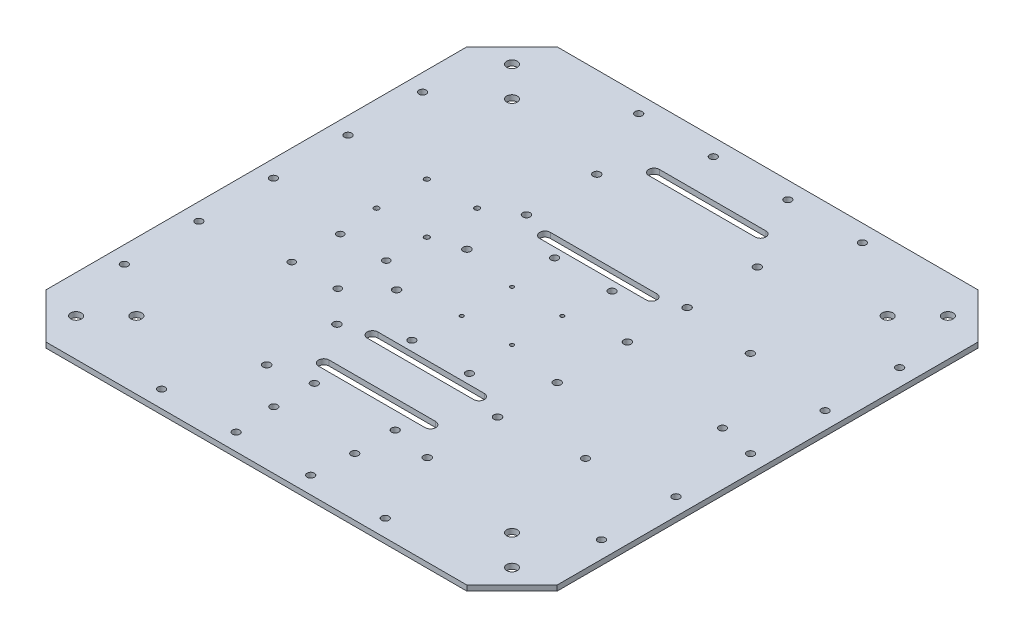
SolidWorks part; units mm, degrees
ref_plane "Front Plane" through (0, 0, 0) normal (0, 0, 1) x (1, 0, 0)
ref_plane "Top Plane" through (0, 0, 0) normal (0, 1, 0) x (1, 0, 0)
ref_plane "Right Plane" through (0, 0, 0) normal (1, 0, 0) x (0, 0, -1)
sketch "Sketch1" plane through (0, 0, 0) normal (0, 1, 0) x (1, 0, 0)
  line L0 (-121.2861, 45.3182) -> (-94.3453, 72.259)
  line L1 (-121.2861, 72.259) -> (183.5139, 72.259)
  line L2 (-121.2861, 72.259) -> (-121.2861, -232.541)
  line L3 (-121.2861, -232.541) -> (183.5139, -232.541)
  line L4 (183.5139, 72.259) -> (183.5139, -232.541)
  line L5 (31.1139, 95.069) -> (31.1139, -294.9418) construction
  line L6 (-146.0448, -80.141) -> (218.038, -80.141) construction
  line L7 (183.5139, 45.3182) -> (156.5732, 72.259)
  line L8 (183.5139, -205.6003) -> (156.5732, -232.541)
  line L9 (-121.2861, -205.6003) -> (-94.3453, -232.541)
  point P8 (31.1139, 72.259)
  point P11 (-121.2861, -80.141)
  dimension "D1" = 304.8
  dimension "D2" = 304.8
  dimension "D3" = 45
  dimension "D4" = 38.1
extrude "Boss-Extrude1" add sketch "Sketch1" along normal blind 3.175
sketch "Sketch2" plane through (0, 3.175, 0) normal (0, 1, 0) x (1, 0, 0)
  line L0 (31.1139, 72.259) -> (31.1139, -287.8465) construction
  line L1 (-94.3453, 72.259) -> (156.5732, 72.259) construction
  line L2 (183.5139, -80.141) -> (-158.2106, -80.141) construction
  line L3 (183.5139, 45.3182) -> (183.5139, -205.6003) construction
  circle A0 centre (13.8419, -37.469) radius 2.159
  circle A1 centre (48.1319, -37.469) radius 2.159
  circle A2 centre (13.8419, -122.559) radius 2.159
  circle A3 centre (48.1319, -122.559) radius 2.159
  dimension "D5" = 4.318
  dimension "D6" = 4.318
  dimension "D7" = 4.318
  dimension "D8" = 4.318
  dimension "D1" = 17.272
  dimension "D2" = 34.29
  dimension "D3" = 85.09
  dimension "D4" = 42.672
extrude "Cut-Extrude1" cut sketch "Sketch2" against normal through all
sketch "Sketch4" plane through (0, 3.175, 0) normal (0, 1, 0) x (1, 0, 0)
  line L0 (-0.6361, 36.294) -> (62.8639, 36.294) construction
  line L1 (-0.6361, 39.469) -> (62.8639, 39.469)
  line L2 (-0.6361, 33.119) -> (62.8639, 33.119)
  line L3 (-0.6361, -28.706) -> (62.8639, -28.706) construction
  line L4 (-0.6361, -25.531) -> (62.8639, -25.531)
  line L5 (-0.6361, -31.881) -> (62.8639, -31.881)
  line L6 (31.1139, 72.259) -> (31.1139, -65.9651) construction
  line L7 (-94.3453, 72.259) -> (156.5732, 72.259) construction
  line L8 (-121.2861, -80.141) -> (257.7387, -80.141) construction
  line L9 (-121.2861, 45.3182) -> (-121.2861, -205.6003) construction
  line L10 (31.1139, -232.541) -> (31.1139, -94.317) construction
  line L11 (-0.6361, -131.576) -> (62.8639, -131.576) construction
  line L12 (-0.6361, -128.401) -> (62.8639, -128.401)
  line L13 (-0.6361, -134.751) -> (62.8639, -134.751)
  line L14 (-0.6361, -160.576) -> (62.8639, -160.576) construction
  line L15 (-0.6361, -157.401) -> (62.8639, -157.401)
  line L16 (-0.6361, -163.751) -> (62.8639, -163.751)
  arc A0 (-0.6361, 39.469) -> (-0.6361, 33.119) centre (-0.6361, 36.294) ccw
  arc A1 (62.8639, 33.119) -> (62.8639, 39.469) centre (62.8639, 36.294) ccw
  arc A2 (-0.6361, -25.531) -> (-0.6361, -31.881) centre (-0.6361, -28.706) ccw
  arc A3 (62.8639, -31.881) -> (62.8639, -25.531) centre (62.8639, -28.706) ccw
  arc A5 (-0.6361, -128.401) -> (-0.6361, -134.751) centre (-0.6361, -131.576) ccw
  arc A6 (62.8639, -134.751) -> (62.8639, -128.401) centre (62.8639, -131.576) ccw
  arc A7 (-0.6361, -157.401) -> (-0.6361, -163.751) centre (-0.6361, -160.576) ccw
  arc A8 (62.8639, -163.751) -> (62.8639, -157.401) centre (62.8639, -160.576) ccw
  point P2 (31.1139, 36.294)
  point P7 (31.1139, -28.706)
  point P28 (31.1139, -131.576)
  point P33 (31.1139, -160.576)
  dimension "D1" = 63.5
  dimension "D2" = 63.5
  dimension "D3" = 6.35
  dimension "D4" = 6.35
  dimension "D5" = 65
  dimension "D6" = 48.26
  dimension "D7" = 63.5
  dimension "D8" = 63.5
  dimension "D9" = 6.35
  dimension "D10" = 6.35
  dimension "D11" = 29
  dimension "D12" = 48.26
extrude "Cut-Extrude2" cut sketch "Sketch4" against normal through all
sketch "Sketch7" plane through (0, 3.175, 0) normal (0, 1, 0) x (1, 0, 0)
  line L0 (-49.9121, 53.9596) -> (-49.9121, -59.6418) construction
  line L1 (-121.2861, -80.141) -> (183.5139, -80.141) construction
  line L2 (-121.2861, 45.3182) -> (-121.2861, -205.6003) construction
  line L3 (183.5139, 45.3182) -> (183.5139, -205.6003) construction
  line L4 (31.1139, 72.259) -> (31.1139, -252.674) construction
  line L5 (-94.3453, 72.259) -> (156.5732, 72.259) construction
  circle A0 centre (-34.9261, -34.929) radius 1.524
  circle A1 centre (-34.9261, -64.901) radius 1.524
  circle A2 centre (-64.8981, -64.901) radius 1.524
  circle A3 centre (-64.8981, -34.929) radius 1.524
  dimension "D1" = 3.048
  dimension "D2" = 14.986
  dimension "D4" = 29.972
  dimension "D3" = 3.048
  dimension "D5" = 15.24
  dimension "D6" = 66.04
  dimension "D7" = 14.986
extrude "Cut-Extrude3" cut sketch "Sketch7" against normal through all
sketch "Sketch8" plane through (0, 3.175, 0) normal (0, 1, 0) x (1, 0, 0)
  line L0 (-94.3453, -232.541) -> (156.5732, -232.541) construction
  line L1 (183.5139, 45.3182) -> (183.5139, -205.6003) construction
  circle A0 centre (73.0239, -207.649) radius 1.524
  circle A1 centre (73.0239, -177.169) radius 1.524
  circle A2 centre (96.8999, -207.649) radius 1.524
  circle A3 centre (96.8999, -177.169) radius 1.524
  dimension "D1" = 3.048
  dimension "D2" = 30.48
  dimension "D3" = 23.876
  dimension "D4" = 24.892
  dimension "D5" = 86.614
extrude "Cut-Extrude4" [suppressed] cut sketch "Sketch8" against normal through all and the other way through all
sketch "Sketch10" plane through (0, 0, 0) normal (0, -1, 0) x (1, 0, 0)
  line L0 (-94.3453, 232.541) -> (156.5732, 232.541) construction
  line L1 (31.1139, 232.541) -> (31.1139, 128.7119) construction
  line L2 (-0.6361, 163.751) -> (62.8639, 163.751) construction
  circle A0 centre (6.9839, 198.041) radius 2.159
  circle A1 centre (55.2439, 198.041) radius 2.159
  circle A2 centre (6.9839, 173.911) radius 2.159
  circle A3 centre (55.2439, 173.911) radius 2.159
  dimension "D1" = 4.318
  dimension "D2" = 48.26
  dimension "D4" = 10.16
  dimension "D6" = 4.318
  dimension "D7" = 4.318
  dimension "D8" = 4.318
  dimension "D3" = 24.13
  dimension "D5" = 24.13
extrude "Cut-Extrude6" cut sketch "Sketch10" against normal through all
sketch "Sketch9" plane through (0, 0, 0) normal (0, -1, 0) x (-1, 0, 0)
  line L1 (121.2861, -80.141) -> (-327.4314, -80.141) construction
  line L2 (48.6421, -47.3693) -> (48.6421, -130.2963) construction
  line L3 (-31.1139, 72.259) -> (-31.1139, -331.7119) construction
  line L4 (94.3453, 72.259) -> (-156.5732, 72.259) construction
  line L7 (121.2861, 45.3182) -> (121.2861, -205.6003) construction
  circle A0 centre (62.3581, -117.987) radius 2.032
  circle A1 centre (34.9261, -117.987) radius 2.032
  circle A2 centre (62.3581, -89.031) radius 2.032
  circle A3 centre (34.9261, -89.031) radius 2.032
  dimension "D1" = 4.064
  dimension "D9" = 4.064
  dimension "D2" = 66.04
  dimension "D3" = 28.956
  dimension "D4" = 8.89
  dimension "D8" = 13.716
extrude "Cut-Extrude5" cut sketch "Sketch9" against normal through all
sketch "Sketch13" plane through (0, 0, 0) normal (0, -1, 0) x (1, 0, 0)
  line L0 (31.1139, -72.259) -> (31.1139, 261.4711) construction
  line L1 (-94.3453, -72.259) -> (156.5732, -72.259) construction
  line L2 (-121.2861, 80.141) -> (239.2508, 80.141) construction
  line L3 (-121.2861, -45.3182) -> (-121.2861, 205.6003) construction
  circle A0 centre (16.1139, 95.141) radius 1.1
  circle A1 centre (16.1139, 65.141) radius 1.1
  circle A2 centre (46.1139, 65.141) radius 1.1
  circle A3 centre (46.1139, 95.141) radius 1.1
  dimension "D1" = 2.2
  dimension "D2" = 2.2
  dimension "D3" = 30
  dimension "D4" = 15
  dimension "D5" = 15
extrude "Cut-Extrude8" cut sketch "Sketch13" against normal through all
sketch "Sketch14" plane through (0, 0, 0) normal (0, -1, 0) x (1, 0, 0)
  line L0 (31.1139, 232.541) -> (31.1139, -154.5354) construction
  line L1 (-94.3453, 232.541) -> (156.5732, 232.541) construction
  line L2 (-121.2861, 80.141) -> (331.9066, 80.141) construction
  line L3 (-121.2861, -45.3182) -> (-121.2861, 205.6003) construction
  line L4 (-121.2861, 205.6003) -> (-94.3453, 232.541) construction
  line L5 (-224.559, -175.5319) -> (286.7869, 335.814) construction
  line L6 (-224.559, -175.5319) -> (286.7869, -175.5319) construction
  line L7 (-224.559, -175.5319) -> (-224.559, 335.814) construction
  line L8 (-121.2861, 205.6003) -> (-94.3453, 232.541) construction
  line L9 (-107.8157, 219.0706) -> (-48.5429, 159.7979) construction
  line L10 (-224.559, 335.814) -> (286.7869, 335.814) construction
  line L11 (286.7869, -175.5319) -> (286.7869, 335.814) construction
  line L12 (286.7869, -175.5319) -> (-224.559, 335.814) construction
  line L14 (-121.2861, -45.3182) -> (-94.3453, -72.259) construction
  line L21 (-224.559, -175.5319) -> (-107.8157, -58.7886) construction
  line L22 (170.0436, -58.7886) -> (286.7869, -175.5319) construction
  line L23 (183.5139, -45.3182) -> (156.5732, -72.259) construction
  line L24 (170.0436, 219.0706) -> (286.7869, 335.814) construction
  line L25 (183.5139, 205.6003) -> (156.5732, 232.541) construction
  line L26 (-224.559, 335.814) -> (-107.8157, 219.0706) construction
  circle A1 centre (-98.8354, 210.0904) radius 3.175
  circle A3 centre (-80.8749, 192.1299) radius 3.175
  circle A4 centre (143.1028, 192.1299) radius 3.175
  circle A7 centre (161.0633, 210.0904) radius 3.175
  circle A8 centre (-98.8354, -49.8083) radius 3.175
  circle A11 centre (-80.8749, -31.8478) radius 3.175
  circle A14 centre (161.0633, -49.8083) radius 3.175
  circle A15 centre (143.1028, -31.8478) radius 3.175
  point P8 (31.1139, 80.141)
  point P30 (286.7869, 80.141)
  point P33 (-107.8157, -58.7886)
  point P36 (31.1139, -175.5319)
  dimension "D3" = 6.35
  dimension "D6" = 6.35
  dimension "D1" = 12.7
  dimension "D2" = 165.1
  dimension "D9" = 25.4
extrude "Cut-Extrude9" cut sketch "Sketch14" against normal through all
sketch "Sketch15" plane through (0, 0, 0) normal (0, -1, 0) x (1, 0, 0)
  line L0 (31.1139, 232.541) -> (31.1139, 125.875) construction
  line L1 (-94.3453, 232.541) -> (156.5732, 232.541) construction
  line L2 (-121.2861, 80.141) -> (75.4631, 80.141) construction
  line L3 (-121.2861, -45.3182) -> (-121.2861, 205.6003) construction
  circle A0 centre (8.8889, 222.381) radius 2.159
  circle A1 centre (-35.5611, 222.381) radius 2.159
  circle A2 centre (-111.1261, 80.141) radius 2.159
  circle A3 centre (-111.1261, 124.591) radius 2.159
  circle A4 centre (-111.1261, 169.041) radius 2.159
  circle A5 centre (173.3539, 169.041) radius 2.159
  circle A6 centre (173.3539, 124.591) radius 2.159
  circle A7 centre (173.3539, 80.141) radius 2.159
  circle A8 centre (97.7889, 222.381) radius 2.159
  circle A9 centre (53.3389, 222.381) radius 2.159
  circle A10 centre (53.3389, -62.099) radius 2.159
  circle A11 centre (97.7889, -62.099) radius 2.159
  circle A12 centre (173.3539, 35.691) radius 2.159
  circle A13 centre (173.3539, -8.759) radius 2.159
  circle A14 centre (-111.1261, -8.759) radius 2.159
  circle A15 centre (-111.1261, 35.691) radius 2.159
  circle A16 centre (-35.5611, -62.099) radius 2.159
  circle A17 centre (8.8889, -62.099) radius 2.159
  dimension "D3" = 4.318
  dimension "D4" = 4.318
  dimension "D8" = 4.318
  dimension "D9" = 4.318
  dimension "D10" = 4.318
  dimension "D1" = 22.225
  dimension "D2" = 44.45
  dimension "D5" = 10.16
  dimension "D6" = 44.45
  dimension "D7" = 44.45
  dimension "D11" = 10.16
extrude "Cut-Extrude10" cut sketch "Sketch15" against normal through all
sketch "Sketch16" plane through (0, 0, 0) normal (0, -1, 0) x (-1, 0, 0)
  line L0 (-31.1139, 72.259) -> (-31.1139, -323.0503) construction
  line L1 (-101.2179, -121.924) -> (-141.8579, -121.924)
  line L2 (-101.2179, -121.924) -> (-101.2179, -38.358)
  line L3 (-101.2179, -38.358) -> (-141.8579, -38.358)
  line L4 (-141.8579, -121.924) -> (-141.8579, -38.358)
  line L6 (94.3453, 72.259) -> (-156.5732, 72.259) construction
  line L7 (121.2861, -80.141) -> (-312.3855, -80.141) construction
  line L8 (121.2861, 45.3182) -> (121.2861, -205.6003) construction
  circle A0 centre (-126.6179, -131.83) radius 2.159
  circle A1 centre (-121.5379, -28.452) radius 2.159
  circle A2 centre (-151.7639, -75.274) radius 2.159
  point P18 (-141.8579, -80.141)
  dimension "D3" = 9.906
  dimension "D4" = 9.906
  dimension "D5" = 9.906
  dimension "D6" = 15.24
  dimension "D7" = 20.32
  dimension "D8" = 46.65
  dimension "D9" = 4.318
  dimension "D10" = 4.318
  dimension "D11" = 4.318
  dimension "D1" = 83.566
  dimension "D2" = 40.64
  dimension "D12" = 120.65
  dimension "D13" = 0
extrude "Cut-Extrude11" cut sketch "Sketch16" against normal through all contours A2 | A0 | A1
sketch "Sketch17" plane through (0, 3.175, 0) normal (0, 1, 0) x (1, 0, 0)
  line L2 (31.1139, 72.259) -> (31.1139, -395.818) construction
  line L3 (-94.3453, 72.259) -> (156.5732, 72.259) construction
  line L4 (183.5139, -80.141) -> (-127.1454, -80.141) construction
  line L5 (183.5139, 45.3182) -> (183.5139, -205.6003) construction
  circle A12 centre (78.9929, -178.566) radius 2.2225
  circle A13 centre (-16.7651, -178.566) radius 2.2225
  circle A14 centre (78.9929, -136.656) radius 2.2225
  circle A15 centre (-16.7651, -136.656) radius 2.2225
  circle A16 centre (78.9929, -101.096) radius 2.2225
  circle A17 centre (-16.7651, -101.096) radius 2.2225
  circle A18 centre (78.9929, -59.186) radius 2.2225
  circle A19 centre (-16.7651, -59.186) radius 2.2225
  circle A20 centre (78.9929, -23.626) radius 2.2225
  circle A21 centre (-16.7651, -23.626) radius 2.2225
  circle A22 centre (78.9929, 18.284) radius 2.2225
  circle A23 centre (-16.7651, 18.284) radius 2.2225
  circle A24 centre (-16.7651, 18.284) radius 2.2225
  circle A25 centre (78.9929, 18.284) radius 2.2225
  circle A26 centre (-16.7651, -23.626) radius 2.2225
  circle A27 centre (78.9929, -23.626) radius 2.2225
  circle A28 centre (-16.7651, -59.186) radius 2.2225
  circle A29 centre (78.9929, -59.186) radius 2.2225
  circle A30 centre (-16.7651, -101.096) radius 2.2225
  circle A31 centre (78.9929, -101.096) radius 2.2225
  circle A32 centre (-16.7651, -136.656) radius 2.2225
  circle A33 centre (78.9929, -136.656) radius 2.2225
  circle A34 centre (-16.7651, -178.566) radius 2.2225
  dimension "D1" = 4.445
  dimension "D2" = 4.445
  dimension "D3" = 4.445
  dimension "D4" = 4.445
  dimension "D5" = 4.445
  dimension "D6" = 4.445
  dimension "D7" = 4.445
  dimension "D8" = 4.445
  dimension "D9" = 4.445
  dimension "D10" = 4.445
  dimension "D11" = 4.445
  dimension "D12" = 4.445
  dimension "D25" = 56.515
  dimension "D24" = 56.515
  dimension "D13" = 95.758
  dimension "D14" = 41.91
  dimension "D15" = 95.758
  dimension "D16" = 41.91
  dimension "D17" = 95.758
  dimension "D18" = 41.91
  dimension "D19" = 47.879
  dimension "D20" = 47.879
  dimension "D21" = 47.879
  dimension "D22" = 20.955
extrude "Cut-Extrude13" cut sketch "Sketch17" against normal through all contours A23 | A22 | A20 | A21 | A18 | A19 | A17 | A16 | A12 | A14 | A15 | A13
